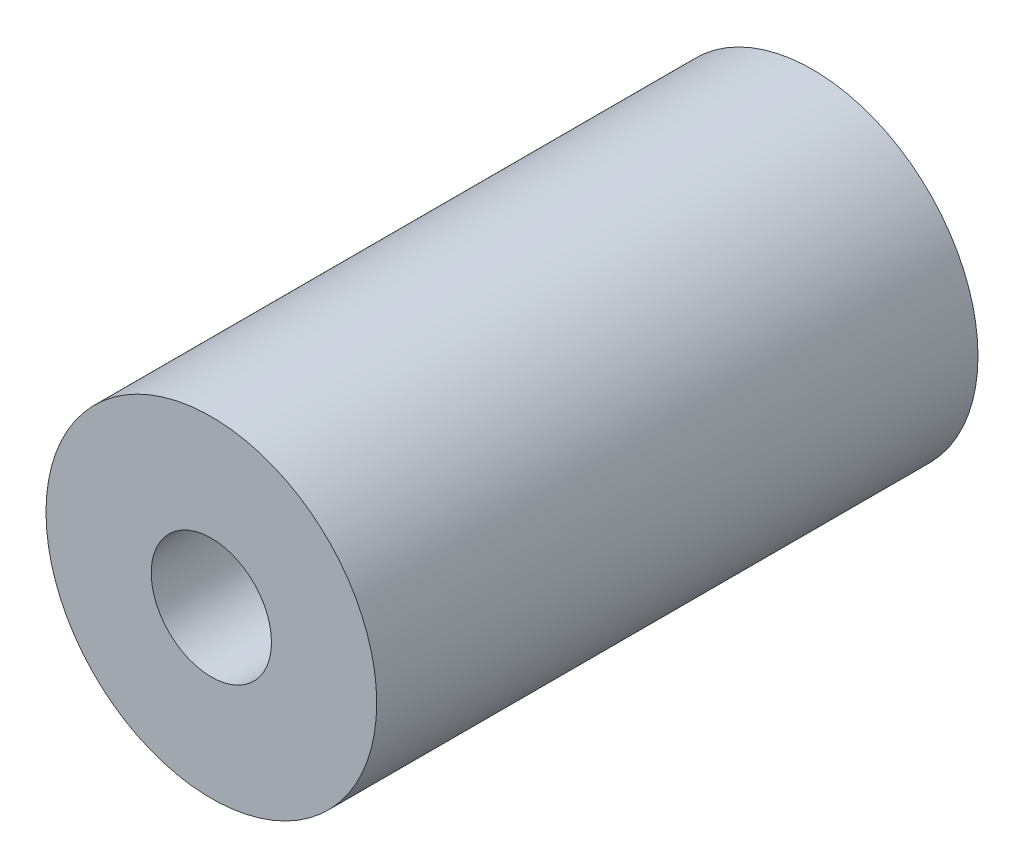
SolidWorks part; units mm, degrees
ref_plane "Front Plane" through (0, 0, 0) normal (0, 0, 1) x (1, 0, 0)
ref_plane "Top Plane" through (0, 0, 0) normal (0, 1, 0) x (1, 0, 0)
ref_plane "Right Plane" through (0, 0, 0) normal (1, 0, 0) x (0, 0, -1)
sketch "Sketch1" plane through (0, 0, 0) normal (0, 0, 1) x (1, 0, 0)
  circle A0 centre (0, 0) radius 6.985
  circle A1 centre (0, 0) radius 2.54
  dimension "D1" = 5.08
  dimension "D2" = 13.97
extrude "Boss-Extrude1" add sketch "Sketch1" along normal blind 25.4
